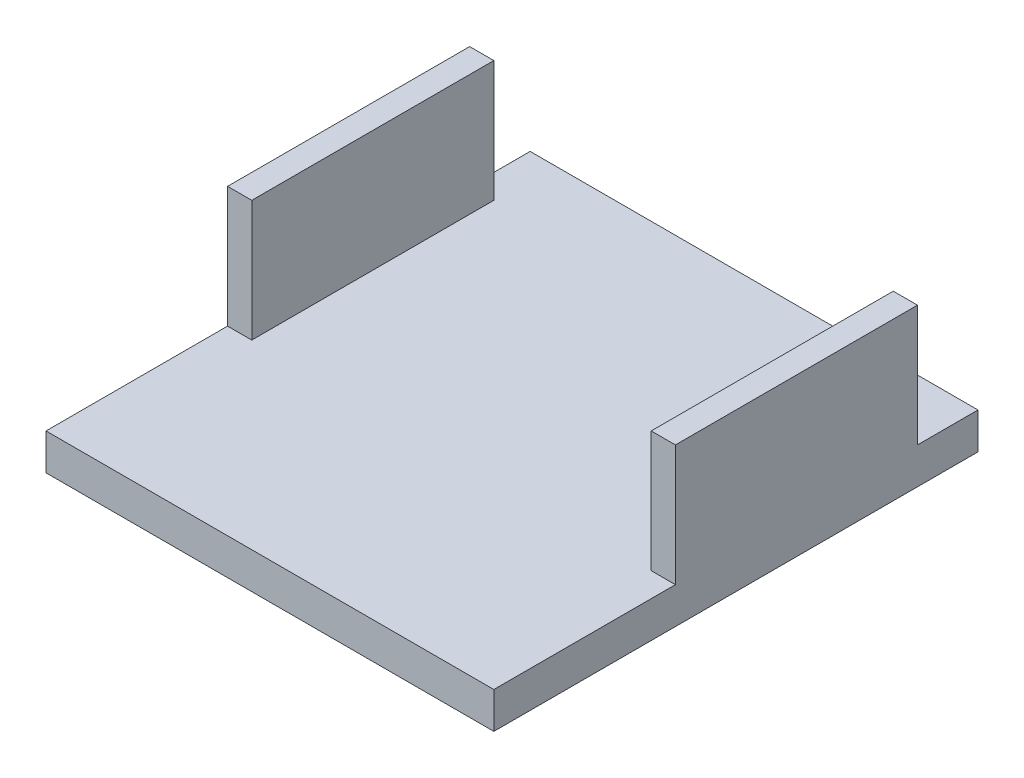
SolidWorks part; units mm, degrees
ref_plane "前视基准面" through (0, 0, 0) normal (0, 0, 1) x (1, 0, 0)
ref_plane "上视基准面" through (0, 0, 0) normal (0, 1, 0) x (1, 0, 0)
ref_plane "右视基准面" through (0, 0, 0) normal (1, 0, 0) x (0, 0, -1)
sketch "草图1" plane through (0, 0, 0) normal (0, 1, 0) x (1, 0, 0)
  line L1 (0, 0) -> (37, 0)
  line L2 (0, 0) -> (0, 40)
  line L3 (0, 40) -> (37, 40)
  line L4 (37, 0) -> (37, 40)
  dimension "D1" = 37
  dimension "D2" = 40
extrude "凸台-拉伸1" add sketch "草图1" along normal blind 3
sketch "草图2" plane through (0, 3, 0) normal (0, 1, 0) x (1, 0, 0)
  line L0 (37, 0) -> (37, 40) construction
  line L1 (37, 35) -> (35, 35)
  line L2 (37, 35) -> (37, 15)
  line L3 (37, 15) -> (35, 15)
  line L4 (35, 35) -> (35, 15)
  line L5 (37, 40) -> (0, 40) construction
  line L6 (0, 40) -> (0, 0) construction
  line L7 (0, 35) -> (2, 35)
  line L8 (0, 35) -> (0, 15)
  line L9 (0, 15) -> (2, 15)
  line L10 (2, 35) -> (2, 15)
  dimension "D1" = 2
  dimension "D2" = 20
  dimension "D3" = 5
  dimension "D4" = 20
  dimension "D5" = 2
  dimension "D6" = 5
extrude "凸台-拉伸2" add sketch "草图2" along normal blind 10
